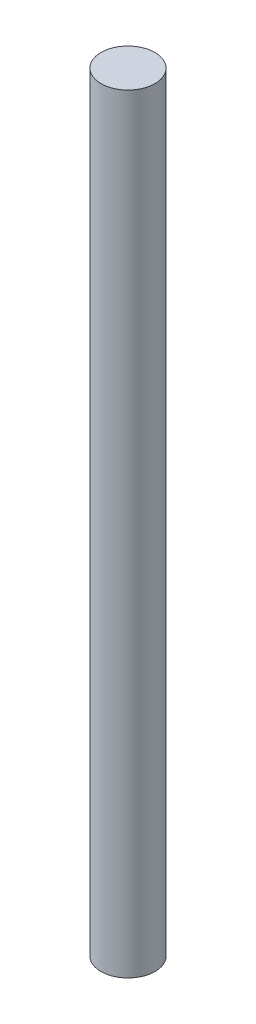
SolidWorks part; units mm, degrees
ref_plane "Front Plane" through (0, 0, 0) normal (0, 0, 1) x (1, 0, 0)
ref_plane "Top Plane" through (0, 0, 0) normal (0, 1, 0) x (1, 0, 0)
ref_plane "Right Plane" through (0, 0, 0) normal (1, 0, 0) x (0, 0, -1)
sketch "Sketch1" plane through (0, 0, 0) normal (0, 1, 0) x (1, 0, 0)
  circle A0 centre (0, 0) radius 6.35
  dimension "D1" = 12.7
extrude "Boss-Extrude1" add sketch "Sketch1" along normal blind 180.975
